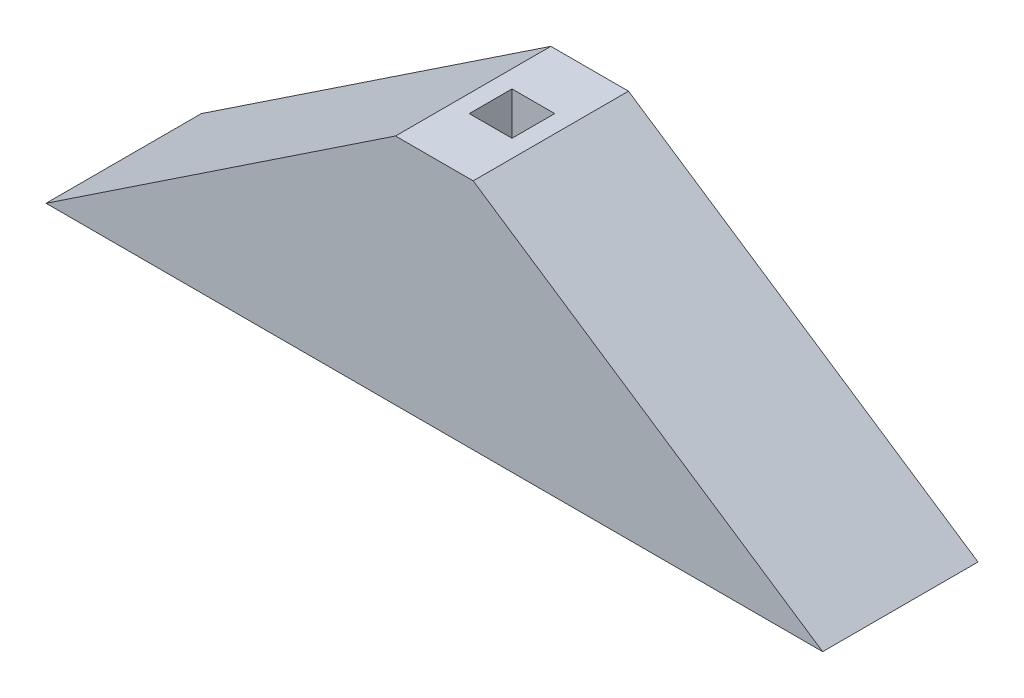
SolidWorks part; units mm, degrees
ref_plane "Front Plane" through (0, 0, 0) normal (0, 0, 1) x (1, 0, 0)
ref_plane "Top Plane" through (0, 0, 0) normal (0, 1, 0) x (1, 0, 0)
ref_plane "Right Plane" through (0, 0, 0) normal (1, 0, 0) x (0, 0, -1)
sketch "Sketch1" plane through (0, 0, 0) normal (0, 0, 1) x (1, 0, 0)
  line L0 (-127, 0) -> (127, 0)
  line L1 (127, 0) -> (12.7, 76.2)
  line L2 (12.7, 76.2) -> (-12.7, 76.2)
  line L3 (-12.7, 76.2) -> (-127, 0)
  line L4 (0, 76.2) -> (0, 0) construction
  point P2 (0, 0)
  point P6 (0, 76.2)
  dimension "D1" = 254
  dimension "D2" = 76.2
  dimension "D3" = 25.4
extrude "Boss-Extrude1" add sketch "Sketch1" along normal blind 50.8
sketch "Sketch2" plane through (0, 76.2, 0) normal (0, 1, 0) x (1, 0, 0)
  line L0 (-12.7, -50.8) -> (12.7, 0) construction
  line L1 (-6.985, -32.385) -> (6.985, -32.385)
  line L2 (-6.985, -32.385) -> (-6.985, -18.415)
  line L3 (-6.985, -18.415) -> (6.985, -18.415)
  line L4 (6.985, -32.385) -> (6.985, -18.415)
  line L5 (-6.985, -32.385) -> (6.985, -18.415) construction
  line L6 (-6.985, -18.415) -> (6.985, -32.385) construction
  line L7 (-12.7, 0) -> (12.7, -50.8) construction
  point P0 (0, -25.4)
  dimension "D1" = 13.97
  dimension "D2" = 13.97
extrude "Cut-Extrude1" cut sketch "Sketch2" against normal blind 63.5
